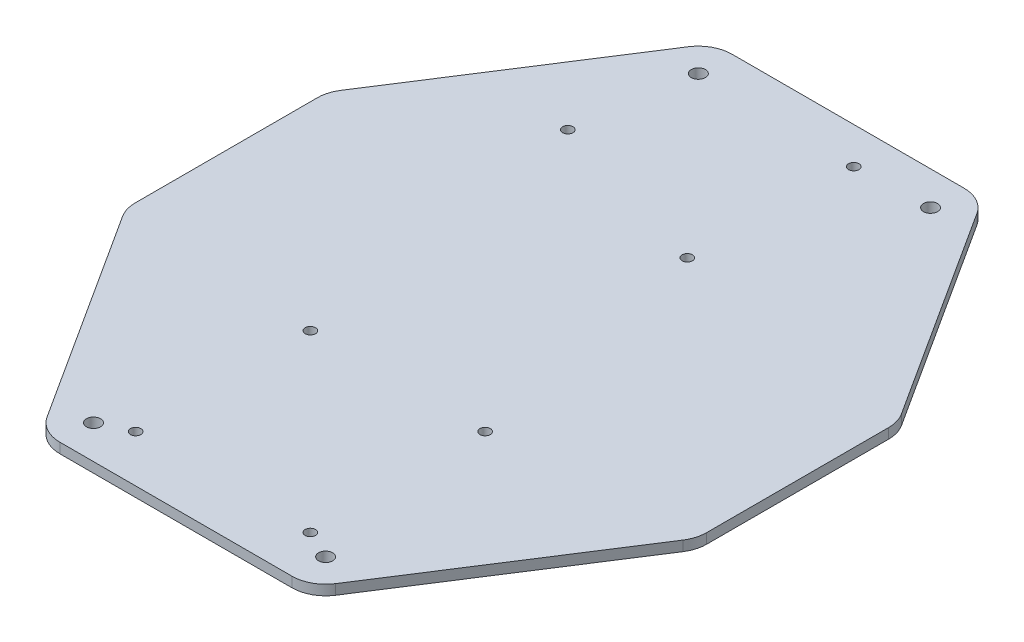
SolidWorks part; units mm, degrees
ref_plane "前视基准面" through (0, 0, 0) normal (0, 0, 1) x (1, 0, 0)
ref_plane "上视基准面" through (0, 0, 0) normal (0, 1, 0) x (1, 0, 0)
ref_plane "右视基准面" through (0, 0, 0) normal (1, 0, 0) x (0, 0, -1)
sketch "草图1" plane through (0, 0, 0) normal (0, 1, 0) x (1, 0, 0)
  line L0 (0, 30) -> (0, 90) construction
  line L5 (0, 90) -> (0, 160) construction
  line L6 (-85, 30) -> (85, 30) construction
  line L7 (-26, -26) -> (26, -26) construction
  line L8 (-26, -26) -> (-26, 26) construction
  line L9 (-26, 26) -> (26, 26) construction
  line L10 (26, -26) -> (26, 26) construction
  line L11 (0, 30) -> (0, -40) construction
  line L12 (-85, 32.937) -> (-85, 87.063)
  line L13 (85, 32.937) -> (85, 87.063)
  line L14 (-34.5405, 160) -> (34.5405, 160)
  line L15 (-34.5405, -40) -> (34.5405, -40)
  line L16 (42.9523, 155.4076) -> (83.4118, 92.4706)
  line L17 (83.4118, 27.5294) -> (42.9523, -35.4076)
  line L18 (-83.4118, 27.5294) -> (-42.9523, -35.4076)
  line L19 (-42.9523, 155.4076) -> (-83.4118, 92.4706)
  line L20 (-40, 160) -> (12.57, 160) construction
  line L21 (12.57, 160) -> (12.57, 149.13) construction
  line L22 (-40, 160) -> (-40, 100.87) construction
  line L23 (-40, 100.87) -> (11.3, 100.87) construction
  line L24 (-40, 160) -> (-40, 116.11) construction
  line L25 (-40, 116.11) -> (-39.5, 116.11) construction
  circle A0 centre (-26, 26) radius 1.55
  circle A1 centre (26, 26) radius 1.55
  circle A2 centre (26, -26) radius 1.55
  circle A3 centre (-26, -26) radius 1.55
  circle A4 centre (-39.5, 116.11) radius 1.55
  circle A5 centre (11.3, 100.87) radius 1.55
  circle A6 centre (12.57, 149.13) radius 1.55
  arc A8 (-85, 32.937) -> (-83.4118, 27.5294) centre (-75, 32.937) ccw
  arc A9 (-34.5405, -40) -> (-42.9523, -35.4076) centre (-34.5405, -30) cw
  arc A10 (34.5405, -40) -> (42.9523, -35.4076) centre (34.5405, -30) ccw
  arc A11 (85, 32.937) -> (83.4118, 27.5294) centre (75, 32.937) cw
  arc A12 (85, 87.063) -> (83.4118, 92.4706) centre (75, 87.063) ccw
  arc A13 (34.5405, 160) -> (42.9523, 155.4076) centre (34.5405, 150) cw
  arc A14 (-34.5405, 160) -> (-42.9523, 155.4076) centre (-34.5405, 150) ccw
  arc A15 (-85, 87.063) -> (-83.4118, 92.4706) centre (-75, 87.063) cw
  circle A16 centre (-34.5405, -30) radius 2.1
  circle A17 centre (34.5405, -30) radius 2.1
  circle A18 centre (34.5405, 150) radius 2.1
  circle A19 centre (-34.5405, 150) radius 2.1
  point P0 (0, 0)
  point P5 (0, 0)
  point P21 (0, 0)
  point P22 (0, 160)
  point P25 (0, 30)
  point P27 (0, -40)
  point P28 (-30, 30)
  point P47 (40, -40)
  point P53 (85, 90)
  point P56 (40, 160)
  point P62 (-85, 90)
  dimension "D3" = 3.1
  dimension "D5" = 60
  dimension "D18" = 3.1
  dimension "D19" = 3.1
  dimension "D20" = 3.1
  dimension "D21" = 10
  dimension "D22" = 4.2
  dimension "D23" = 4.2
  dimension "D24" = 4.2
  dimension "D25" = 4.2
  dimension "D1" = 60
  dimension "D2" = 52
  dimension "D6" = 60
  dimension "D7" = 70
  dimension "D8" = 85
  dimension "D9" = 70
  dimension "D10" = 40
  dimension "D11" = 40
  dimension "D12" = 52.57
  dimension "D13" = 10.87
  dimension "D14" = 59.13
  dimension "D15" = 51.3
  dimension "D16" = 43.89
  dimension "D17" = 0.5
  dimension "D4" = 4
extrude "凸台-拉伸1" add sketch "草图1" along normal blind 3
